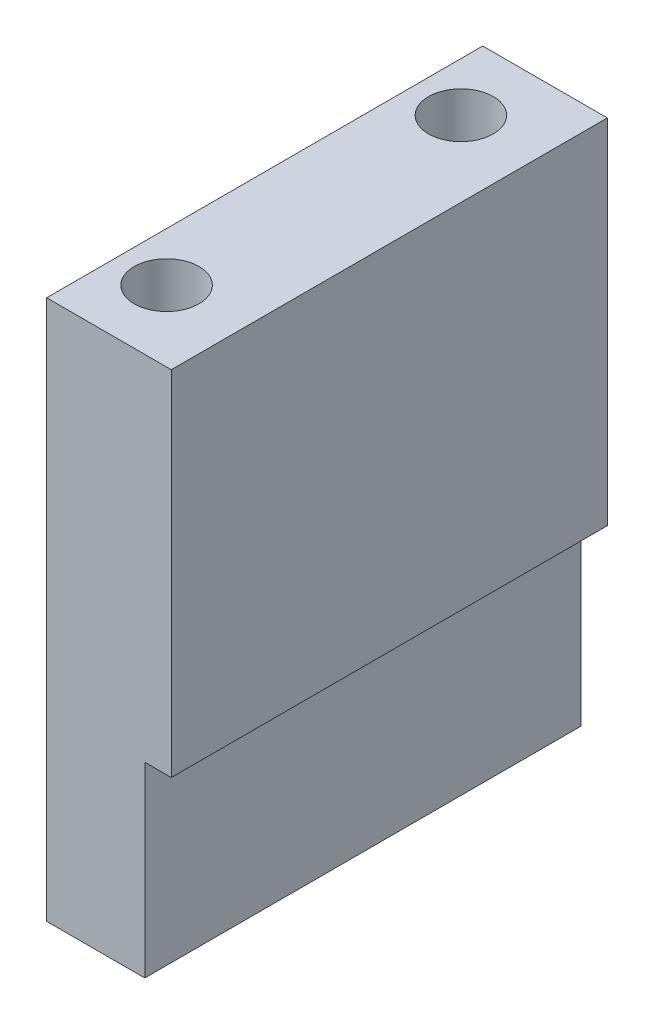
SolidWorks part; units mm, degrees
material "Low Carbon Steel"
ref_plane "Front Plane" through (0, 0, 0) normal (0, 0, 1) x (1, 0, 0)
ref_plane "Top Plane" through (0, 0, 0) normal (0, 1, 0) x (1, 0, 0)
ref_plane "Right Plane" through (0, 0, 0) normal (1, 0, 0) x (0, 0, -1)
sketch "Sketch1" plane through (0, 0, 0) normal (1, 0, 0) x (0, 0, -1)
  line L1 (22.225, -27.525) -> (-22.225, -27.525)
  line L2 (22.225, -27.525) -> (22.225, 27.525)
  line L3 (22.225, 27.525) -> (-22.225, 27.525)
  line L4 (-22.225, -27.525) -> (-22.225, 27.525)
  line L5 (22.225, -27.525) -> (-22.225, 27.525) construction
  line L6 (22.225, 27.525) -> (-22.225, -27.525) construction
  point P0 (0, 0)
  dimension "D1" = 55.05
  dimension "D2" = 44.45
extrude "Boss-Extrude1" add sketch "Sketch1" along normal mid plane 12.7
sketch "Sketch2" plane through (0, 0, -22.225) normal (0, 0, -1) x (-1, 0, 0)
  line L0 (6.35, -27.525) -> (6.35, 27.525) construction
  line L1 (-6.35, -27.525) -> (-3.65, -27.525)
  line L2 (-6.35, -27.525) -> (-6.35, -8.475)
  line L3 (-6.35, -8.475) -> (-3.65, -8.475)
  line L4 (-3.65, -27.525) -> (-3.65, -8.475)
  dimension "D1" = 10
  dimension "D2" = 19.05
extrude "Cut-Extrude1" cut sketch "Sketch2" against normal through all
hole_wizard "M6 Clearance Hole1" positions "Sketch3" profile "Sketch4" hole size "M6" standard "Peddi DIN" end condition through all
sketch "Sketch3" plane through (0, -27.525, 0) normal (0, -1, 0) x (-1, 0, 0)
  line L0 (6.35, 15) -> (-3.65, 15) construction
  line L1 (6.35, -22.225) -> (6.35, 22.225) construction
  line L2 (-3.65, -22.225) -> (-3.65, 22.225) construction
  point P0 (1.35, 15)
  point P2 (1.35, -15)
  dimension "D1" = 15
  dimension "D2" = 15
sketch "Sketch4" plane through (-1.35, -27.525, -15) normal (1, 0, 0) x (0, 0, -1)
  line L0 (0, 0) -> (0, 55.05)
  line L1 (0, 55.05) -> (3.3, 55.05)
  line L2 (3.3, 55.05) -> (3.3, 0)
  line L5 (3.3, 0) -> (0, 0)
  line L11 (0, -6.35) -> (0, 107.95) construction
  dimension "Thru Hole Dia." = 6.6
  dimension "Thru Hole Depth" = 55.05
other "Freeze***"
equation "\"D2@Sketch3\"=\"D1@Sketch3\""
